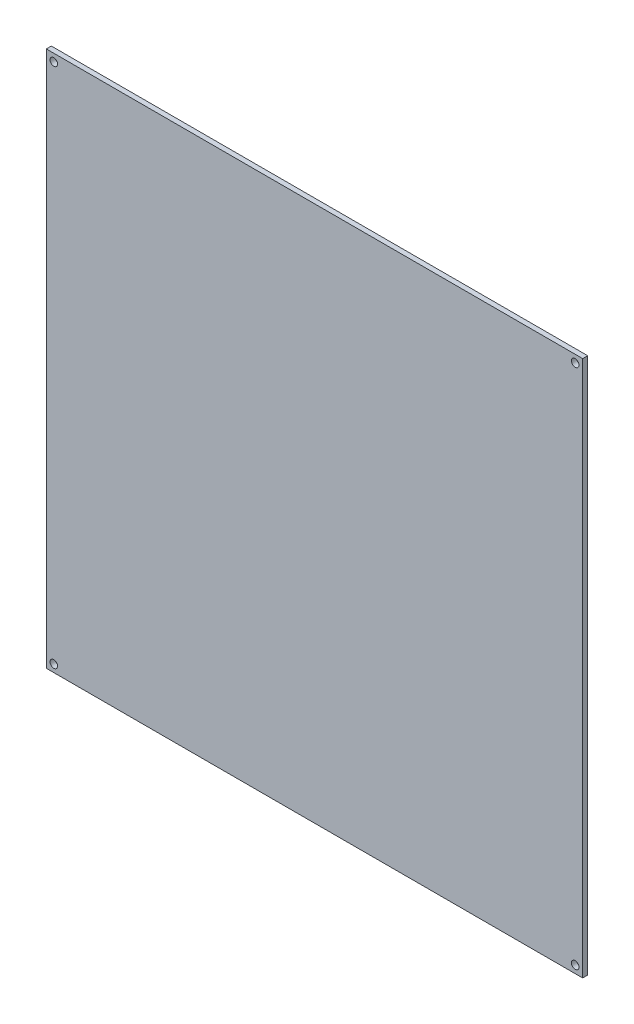
SolidWorks part; units mm, degrees
ref_plane "前视基准面" through (0, 0, 0) normal (0, 0, 1) x (1, 0, 0)
ref_plane "上视基准面" through (0, 0, 0) normal (0, 1, 0) x (1, 0, 0)
ref_plane "右视基准面" through (0, 0, 0) normal (1, 0, 0) x (0, 0, -1)
sketch "草图1" plane through (0, 0, 0) normal (0, 0, 1) x (1, 0, 0)
  line L1 (107, 107) -> (-107, 107)
  line L2 (107, 107) -> (107, -107)
  line L3 (107, -107) -> (-107, -107)
  line L4 (-107, 107) -> (-107, -107)
  line L5 (107, 107) -> (-107, -107) construction
  line L6 (0, 0) -> (-107, 107) construction
  circle A0 centre (104, -104) radius 1.5
  circle A1 centre (104, 104) radius 1.5
  circle A2 centre (-104, 104) radius 1.5
  circle A3 centre (-104, -104) radius 1.5
  point P0 (0, 0)
  point P6 (104, -104)
  dimension "D5" = 2
  dimension "D1" = 214
  dimension "D2" = 214
  dimension "D3" = 3
  dimension "D4" = 3
  dimension "D6" = 2
extrude "凸台-拉伸1" add sketch "草图1" along normal blind 2
